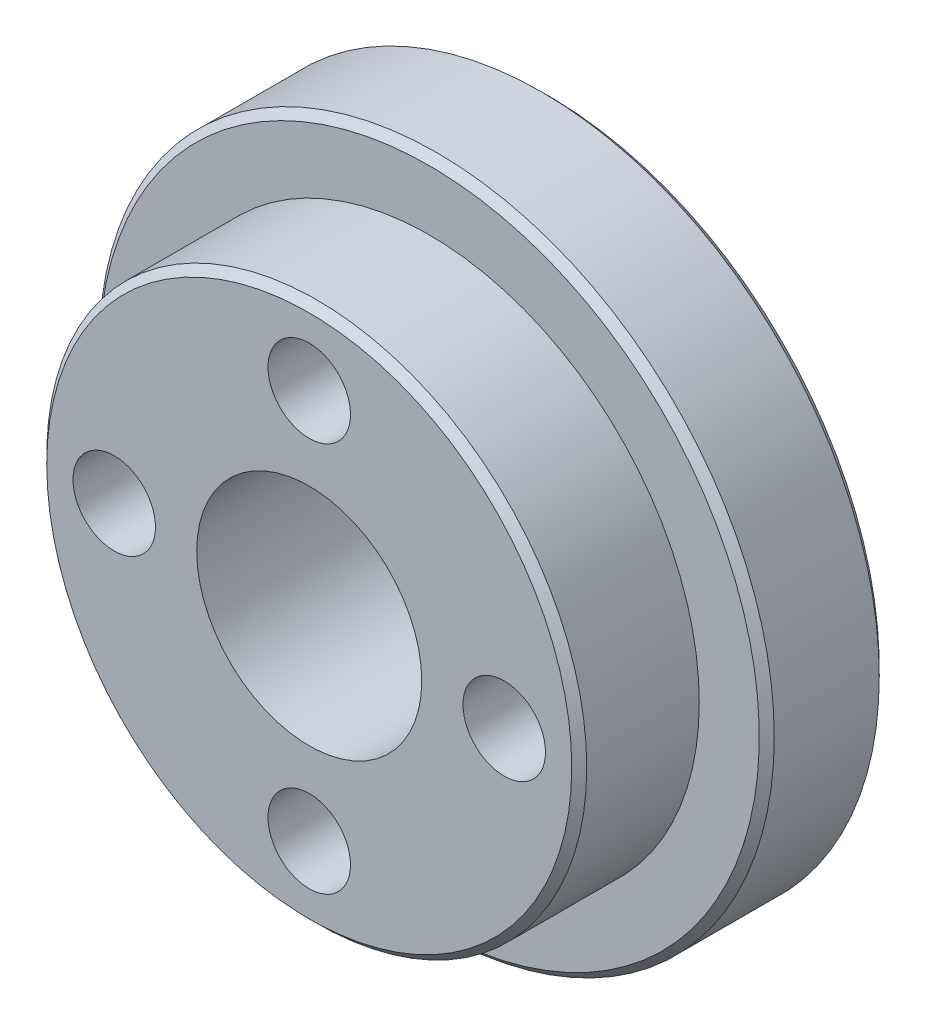
SolidWorks part; units mm, degrees
material "Stainless Steel (ferritic)"
ref_plane "Front Plane" through (0, 0, 0) normal (0, 0, 1) x (1, 0, 0)
ref_plane "Top Plane" through (0, 0, 0) normal (0, 1, 0) x (1, 0, 0)
ref_plane "Right Plane" through (0, 0, 0) normal (1, 0, 0) x (0, 0, -1)
sketch "Sketch1" plane through (0, 0, 0) normal (0, 0, 1) x (1, 0, 0)
  circle A0 centre (0, 0) radius 18
  dimension "D1" = 36
extrude "Boss-Extrude1" add sketch "Sketch1" along normal blind 8
sketch "Sketch2" plane through (0, 0, 0) normal (0, 0, -1) x (-1, 0, 0)
  circle A0 centre (0, 0) radius 22.5
  dimension "D1" = 45
extrude "Boss-Extrude2" add sketch "Sketch2" along normal blind 8
chamfer "Chamfer1" distance 0.5 angle 45 3 edges at (-22.5, 0, -8) (-22.5, 0, 0) (18, 0, 8)
sketch "Sketch3" plane through (0, 0, -8) normal (0, 0, -1) x (-1, 0, 0)
  circle A0 centre (0, 0) radius 7.5
  dimension "D1" = 15
extrude "Cut-Extrude1" cut sketch "Sketch3" against normal through all
hole_wizard "CBORE for M5 SHCS1" positions "Sketch8" profile "Sketch9" counterbore size "M5" standard "ANSI Metric" end condition up to next
sketch "Sketch8" plane through (0, 0, -8) normal (0, 0, -1) x (-1, 0, 0)
  point P0 (0, 13)
  dimension "D1" = 13
sketch "Sketch9" plane through (0, 13, -8) normal (1, 0, 0) x (0, 1, 0)
  line L0 (0, 0) -> (0, 16)
  line L1 (0, 16) -> (2.75, 16)
  line L3 (2.75, 16) -> (2.75, 5)
  line L4 (2.75, 5) -> (4.5, 5)
  line L5 (4.5, 5) -> (4.5, 0)
  line L7 (4.5, 0) -> (0, 0)
  line L11 (0, -6.35) -> (0, 107.95) construction
  dimension "Thru Hole Dia." = 5.5
  dimension "Thru Hole Depth" = 16
  dimension "C'Bore Dia." = 9
  dimension "C'Bore Depth" = 5
pattern_circular "CirPattern1" count 4 over 360 about axis through (0, 0, 0) along (0, 0, 1) of "CBORE for M5 SHCS1"
